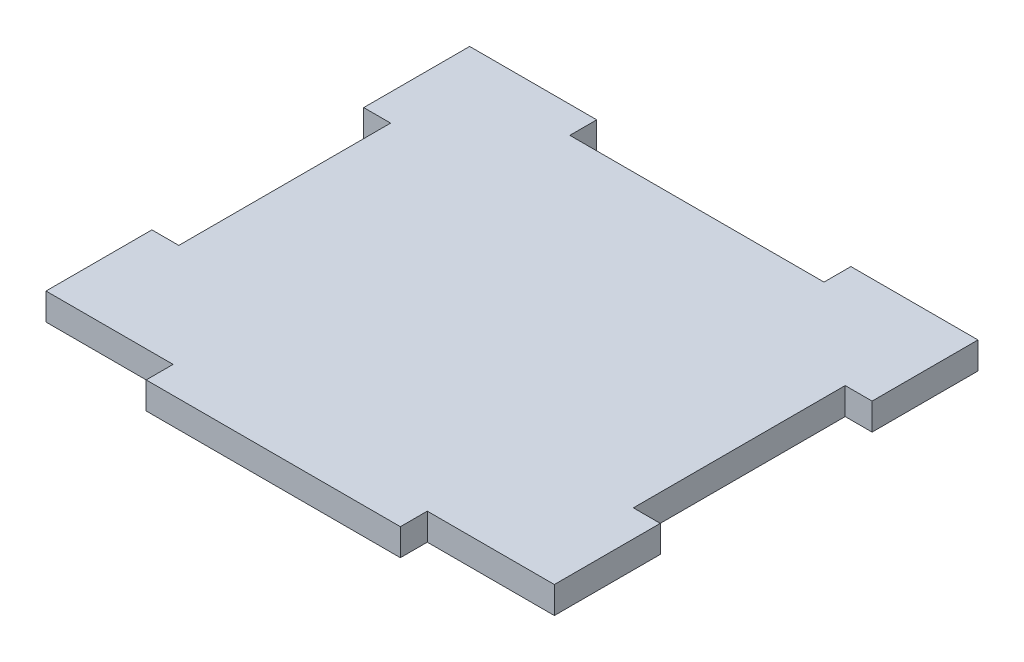
SolidWorks part; units mm, degrees
ref_plane "Front Plane" through (0, 0, 0) normal (0, 0, 1) x (1, 0, 0)
ref_plane "Top Plane" through (0, 0, 0) normal (0, 1, 0) x (1, 0, 0)
ref_plane "Right Plane" through (0, 0, 0) normal (1, 0, 0) x (0, 0, -1)
sketch "Sketch1" plane through (0, 0, 0) normal (0, 1, 0) x (1, 0, 0)
  line L1 (-30, -25) -> (30, -25)
  line L2 (-30, -25) -> (-30, 25)
  line L3 (-30, 25) -> (30, 25)
  line L4 (30, -25) -> (30, 25)
  line L5 (-30, -25) -> (30, 25) construction
  line L6 (-30, 25) -> (30, -25) construction
  point P0 (0, 0)
  dimension "D1" = 60
  dimension "D2" = 50
extrude "Boss-Extrude1" add sketch "Sketch1" along normal blind 3.175
sketch "Sketch2" plane through (0, 3.175, 0) normal (0, 1, 0) x (1, 0, 0)
  line L0 (30, 25) -> (-30, 25) construction
  line L1 (-15, 25) -> (15, 25)
  line L2 (-15, 25) -> (-15, 21.825)
  line L3 (-15, 21.825) -> (15, 21.825)
  line L4 (15, 25) -> (15, 21.825)
  line L5 (-15, 21.825) -> (-30, 21.825) construction
  line L6 (-30, 25) -> (-30, -25) construction
  line L7 (15, 21.825) -> (30, 21.825) construction
  line L8 (30, -25) -> (30, 25) construction
  dimension "D1" = 30
  dimension "D2" = 3.175
extrude "Cut-Extrude1" cut sketch "Sketch2" against normal through all
sketch "Sketch3" plane through (0, 3.175, 0) normal (0, 1, 0) x (1, 0, 0)
  line L0 (-15, 21.825) -> (15, 21.825) construction
  line L1 (15, 21.825) -> (15, 25) construction
  line L2 (-15, 25) -> (-15, 21.825) construction
  line L3 (-30, -25) -> (30, -25) construction
  line L4 (-15, 21.825) -> (15, 21.825)
  line L5 (15, 21.825) -> (15, 25)
  line L6 (-15, 25) -> (-15, 21.825)
  line L7 (-30, -25) -> (30, -25)
  line L8 (-15, 21.825) -> (-15, -25) construction
  line L9 (15, 21.825) -> (15, -25) construction
  line L10 (-15, -25) -> (-15, -28.175)
  line L11 (-15, -28.175) -> (15, -28.175)
  line L12 (15, -28.175) -> (15, -25)
  line L13 (-15, -25) -> (15, -25)
  dimension "D1" = 3.175
extrude "Boss-Extrude2" add sketch "Sketch3" against normal up to surface (3.175 mm away) contours L11 L12 L7 L10 up to face at (0, 0, -11.7063)
sketch "Sketch5" plane through (0, 3.175, 0) normal (0, 1, 0) x (1, 0, 0)
  line L0 (-30, 25) -> (-30, -25) construction
  line L1 (-30, 12.5) -> (-26.825, 12.5)
  line L2 (-30, 12.5) -> (-30, -12.5)
  line L3 (-30, -12.5) -> (-26.825, -12.5)
  line L4 (-26.825, 12.5) -> (-26.825, -12.5)
  line L5 (0, -28.175) -> (0, 21.825) construction
  line L6 (-15, -28.175) -> (15, -28.175) construction
  line L7 (-15, 21.825) -> (15, 21.825) construction
  line L8 (-26.825, 25) -> (-26.825, 12.5) construction
  line L9 (-15, 25) -> (-30, 25) construction
  line L10 (-26.825, -12.5) -> (-26.825, -25) construction
  line L11 (-30, -25) -> (-15, -25) construction
  line L12 (26.825, -12.5) -> (26.825, -25) construction
  line L13 (26.825, 25) -> (26.825, 12.5) construction
  line L14 (26.825, 12.5) -> (26.825, -12.5)
  line L15 (30, -12.5) -> (26.825, -12.5)
  line L16 (30, 12.5) -> (30, -12.5)
  line L17 (30, 12.5) -> (26.825, 12.5)
  dimension "D1" = 3.175
  dimension "D2" = 25
extrude "Cut-Extrude2" cut sketch "Sketch5" against normal blind 3.175
